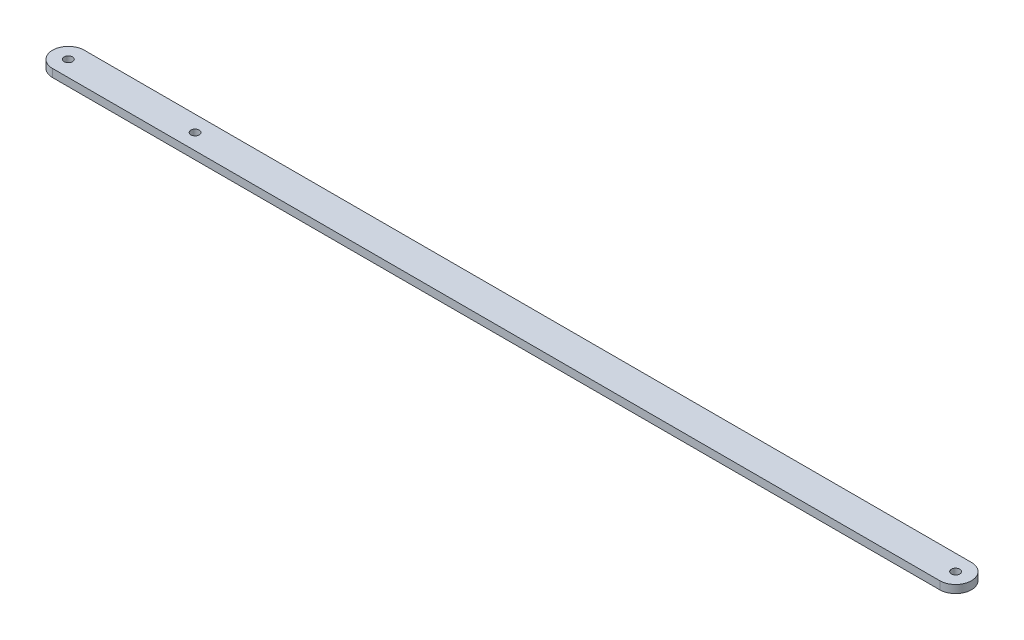
SolidWorks part; units mm, degrees
ref_plane "Front Plane" through (0, 0, 0) normal (0, 0, 1) x (1, 0, 0)
ref_plane "Top Plane" through (0, 0, 0) normal (0, 1, 0) x (1, 0, 0)
ref_plane "Right Plane" through (0, 0, 0) normal (1, 0, 0) x (0, 0, -1)
sketch "Sketch1" plane through (0, 0, 0) normal (0, 1, 0) x (1, 0, 0)
  line L0 (-355.6, 0) -> (355.6, 0) construction
  line L1 (-355.6, 12.7) -> (355.6, 12.7)
  line L2 (-355.6, -12.7) -> (355.6, -12.7)
  arc A0 (-355.6, 12.7) -> (-355.6, -12.7) centre (-355.6, 0) ccw
  arc A1 (355.6, -12.7) -> (355.6, 12.7) centre (355.6, 0) ccw
  circle A2 centre (355.6, 0) radius 3.3655
  circle A3 centre (-254, 0) radius 3.3655
  circle A4 centre (-355.6, 0) radius 3.3655
  point P2 (0, 0)
  dimension "D3" = 6.731
  dimension "D5" = 6.731
  dimension "D6" = 6.731
  dimension "D1" = 711.2
  dimension "D2" = 25.4
  dimension "D4" = 101.6
extrude "Boss-Extrude1" add sketch "Sketch1" along normal blind 6.35
